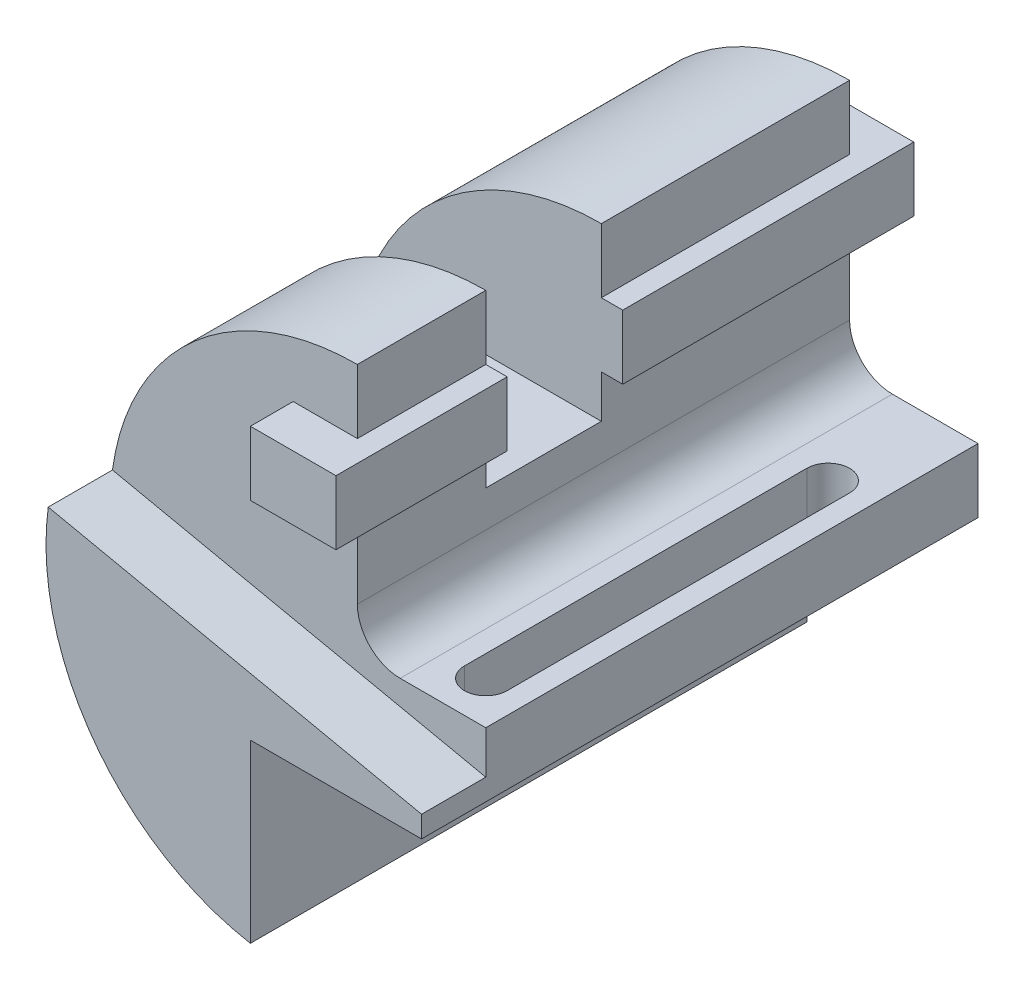
SolidWorks part; units mm, degrees
material "1060 Alloy"
ref_plane "Front Plane" through (0, 0, 0) normal (0, 0, 1) x (1, 0, 0)
ref_plane "Top Plane" through (0, 0, 0) normal (0, 1, 0) x (1, 0, 0)
ref_plane "Right Plane" through (0, 0, 0) normal (1, 0, 0) x (0, 0, -1)
sketch "Sketch1" plane through (0, 0, 0) normal (0, 0, 1) x (1, 0, 0)
  line L0 (0, 0) -> (0, 41.1276)
  line L1 (0, 41.1276) -> (40, 41.1276)
  line L2 (40, 41.1276) -> (40, 56.1276)
  line L3 (40, 56.1276) -> (20, 56.1276)
  line L4 (10, 66.1276) -> (10, 114.6276)
  arc A0 (20, 56.1276) -> (10, 66.1276) centre (20, 66.1276) cw
  arc A1 (10, 114.6276) -> (0, 0) centre (10, 56.8776) ccw
  dimension "D3" = 20
  dimension "D5" = 58.5
  dimension "D6" = 57.75
  dimension "D1" = 40
  dimension "D2" = 15
  dimension "D4" = 10
extrude "Boss-Extrude1" add sketch "Sketch1" along normal blind 115
sketch "Sketch5" plane through (10, 0, 0) normal (1, 0, 0) x (0, 0, -1)
  line L0 (0, 99.6276) -> (10, 99.6276)
  line L1 (0, 66.1276) -> (0, 114.6276) construction
  line L2 (10, 99.6276) -> (10, 84.6276)
  line L3 (10, 84.6276) -> (-125, 84.6276)
  line L4 (-125, 84.6276) -> (-125, 99.6276)
  line L5 (-125, 99.6276) -> (0, 99.6276)
  dimension "D1" = 10
  dimension "D2" = 15
  dimension "D3" = 15
  dimension "D4" = 10
extrude "Boss-Extrude2" add sketch "Sketch5" along normal blind 5 and the other way blind 15
sketch "Sketch8" plane through (0, 0, 0) normal (1, 0, 0) x (0, 0, -1)
  line L0 (-85, 114.6276) -> (-85, 74.6276)
  line L1 (-115, 114.6276) -> (0, 114.6276) construction
  line L2 (-85, 74.6276) -> (-58, 74.6276)
  line L3 (-58, 74.6276) -> (-58, 114.6276)
  line L4 (-58, 114.6276) -> (-85, 114.6276)
  dimension "D1" = 15
  dimension "D2" = 30
  dimension "D3" = 40
  dimension "D4" = 27
extrude "Cut-Extrude1" cut sketch "Sketch8" against normal through all and the other way through all
sketch "Sketch9" plane through (0, 0, 115) normal (0, 0, 1) x (1, 0, 0)
  line L0 (40, 46.1276) -> (-47.2222, 64.6673)
  line L1 (40, 41.1276) -> (40, 56.1276) construction
  line L2 (0, 0) -> (0, 41.1276)
  line L3 (0, 41.1276) -> (40, 41.1276)
  line L4 (40, 41.1276) -> (40, 46.1276)
  line L5 (40, 41.1276) -> (40, 113.0298) construction
  arc A0 (10, 114.6276) -> (0, 0) centre (10, 56.8776) ccw construction
  arc A1 (-47.2222, 64.6673) -> (0, 0) centre (10, 56.8776) ccw
  dimension "D1" = 78
  dimension "D2" = 5
extrude "Boss-Extrude3" add sketch "Sketch9" along normal blind 15
sketch "Sketch10" plane through (0, 56.1276, 0) normal (0, 1, 0) x (1, 0, 0)
  line L0 (30, -105) -> (30, -25) construction
  line L1 (25, -105) -> (25, -25)
  line L2 (35, -105) -> (35, -25)
  line L3 (40, -115) -> (20, -115) construction
  line L4 (40, -115) -> (40, 0) construction
  arc A0 (25, -105) -> (35, -105) centre (30, -105) ccw
  arc A1 (35, -25) -> (25, -25) centre (30, -25) ccw
  point P2 (30, -65)
  dimension "D4" = 10
  dimension "D1" = 10
  dimension "D2" = 80
  dimension "D3" = 10
extrude "Cut-Extrude2" cut sketch "Sketch10" against normal through all contours L2 A1 L1 A0
